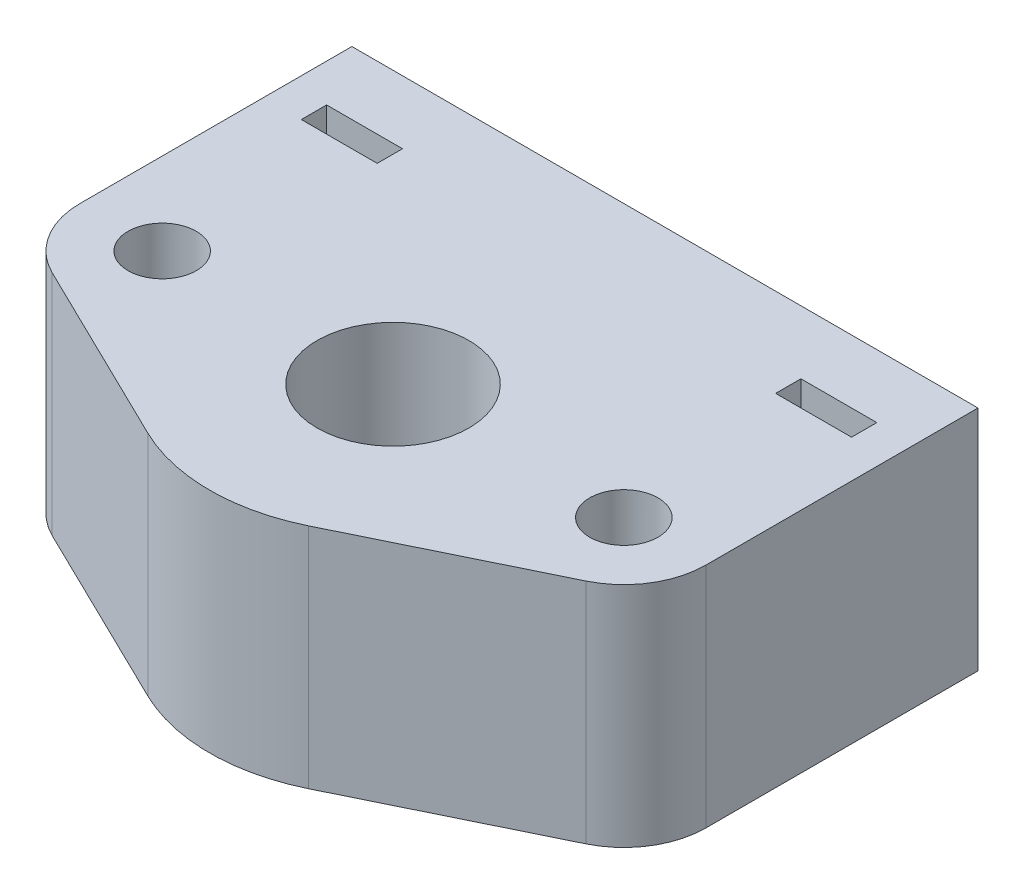
SolidWorks part; units mm, degrees
ref_plane "Front Plane" through (0, 0, 0) normal (0, 0, 1) x (1, 0, 0)
ref_plane "Top Plane" through (0, 0, 0) normal (0, 1, 0) x (1, 0, 0)
ref_plane "Right Plane" through (0, 0, 0) normal (1, 0, 0) x (0, 0, -1)
sketch "Sketch1" plane through (0, 0, 0) normal (0, 1, 0) x (1, 0, 0)
  line L0 (-24.75, 0) -> (-24.75, -21.5)
  line L2 (-24.75, 0) -> (0, 0)
  line L3 (0, 0) -> (0, -15.5)
  line L4 (0, -27.5) -> (0, -36)
  line L7 (-21.0993, -27.3422) -> (-6.3562, -34.5326)
  line L9 (-18.25, -21.5) -> (0, -21.5) construction
  circle A0 centre (-18.25, -21.5) radius 2.7
  arc A1 (0, -15.5) -> (0, -27.5) centre (0, -21.5) ccw
  arc A2 (-6.3562, -34.5326) -> (0, -36) centre (0, -21.5) ccw
  arc A3 (-24.75, -21.5) -> (-21.0993, -27.3422) centre (-18.25, -21.5) ccw
  dimension "D3" = 6
  dimension "D6" = 14.5
  dimension "D7" = 6.5
  dimension "D2" = 5.4
  dimension "D1" = 21.5
  dimension "D8" = 18.25
extrude "Boss-Extrude1" add sketch "Sketch1" along normal blind 12 and the other way blind 6
sketch "Sketch3" plane through (0, 0, 0) normal (0, 0, -1) x (-1, 0, 0)
  line L0 (0, -6) -> (0, 12) construction
  line L2 (18.75, 12) -> (18.75, 6) construction
  line L3 (0, 12) -> (24.75, 12) construction
  line L4 (18.75, 6) -> (24.75, 6) construction
  line L5 (24.75, 12) -> (24.75, -6) construction
  line L6 (0, 1.7) -> (0, -1.7)
  circle A0 centre (18.75, 6) radius 1.7
  arc A1 (0, 1.7) -> (0, -1.7) centre (0, 0) cw
  dimension "D1" = 3.4
  dimension "D2" = 6
extrude "Cut-Extrude1" cut sketch "Sketch3" against normal blind 10
sketch "Sketch4" plane through (0, 0, 0) normal (0, 0, -1) x (-1, 0, 0)
  line L0 (15.75, 9) -> (15.75, 12)
  line L1 (15.75, 3) -> (21.75, 3)
  line L2 (15.75, 3) -> (15.75, 9)
  line L3 (15.75, 9) -> (21.75, 9) construction
  line L4 (21.75, 3) -> (21.75, 9)
  line L5 (15.75, 3) -> (21.75, 9) construction
  line L6 (15.75, 9) -> (21.75, 3) construction
  line L7 (0, 12) -> (24.75, 12) construction
  line L8 (21.75, 9) -> (21.75, 12)
  line L9 (21.75, 12) -> (15.75, 12)
  line L10 (0, 3) -> (3, 3)
  line L11 (0, 1.7) -> (0, 12) construction
  line L12 (3, 3) -> (3, 0)
  line L13 (0, -6) -> (24.75, -6) construction
  line L14 (3, -6) -> (0, -6)
  line L15 (0, -6) -> (0, 3)
  line L16 (3, 0) -> (3, -6)
  line L17 (0, 0) -> (3, 0) construction
  point P0 (18.75, 6)
  dimension "D1" = 6
  dimension "D2" = 3
extrude "Cut-Extrude2" cut sketch "Sketch4" against normal blind 2 from offset 5 offset against normal yes
sketch "Sketch6" plane through (0, -6, 0) normal (0, -1, 0) x (1, 0, 0)
  line L1 (-14, 23.9537) -> (-18.25, 26.4075)
  line L2 (-18.25, 26.4075) -> (-22.5, 23.9537)
  line L3 (-22.5, 23.9537) -> (-22.5, 19.0463)
  line L4 (-22.5, 19.0463) -> (-18.25, 16.5925)
  line L5 (-18.25, 16.5925) -> (-14, 19.0463)
  line L6 (-14, 19.0463) -> (-14, 23.9537)
  circle A0 centre (-18.25, 21.5) radius 4.25 construction
  dimension "D1" = 8.5
extrude "Cut-Extrude3" cut sketch "Sketch6" against normal blind 10
mirror "Mirror1" about plane through (0, -6, 0) normal (1, 0, 0) of bodies 108 103
equation "\"M3_d\"= 3.4"
equation "\"M3_nut_m\"= 2"
equation "\"M3_nut_s\"= 6"
equation "\"t\"= 3"
equation "\"D1@Boss-Extrude1\"=\"M3_nut_s\" + 2 * \"t\""
equation "\"D1@Sketch3\"=\"M3_d\""
equation "\"D1@Sketch4\"=\"M3_nut_s\""
equation "\"D1@Cut-Extrude2\"=\"M3_nut_m\""
equation "\"D2@Sketch3\"=\"M3_nut_s\" / 2 + \"t\""
equation "\"D19@Cut-Extrude5\"=(10 - \"M3_nut_m\") / 2"
equation "\"D2@Boss-Extrude1\"=0.5 * \"M3_nut_s\" + \"t\""
equation "\"D2@Sketch4\"=\"M3_nut_s\" / 2"
equation "\"M5_d\"= 5.4"
equation "\"D2@Sketch1\"=\"M5_d\""
equation "\"M5_nut_s\"= 8.5"
equation "\"D1@Sketch6\"=\"M5_nut_s\""
